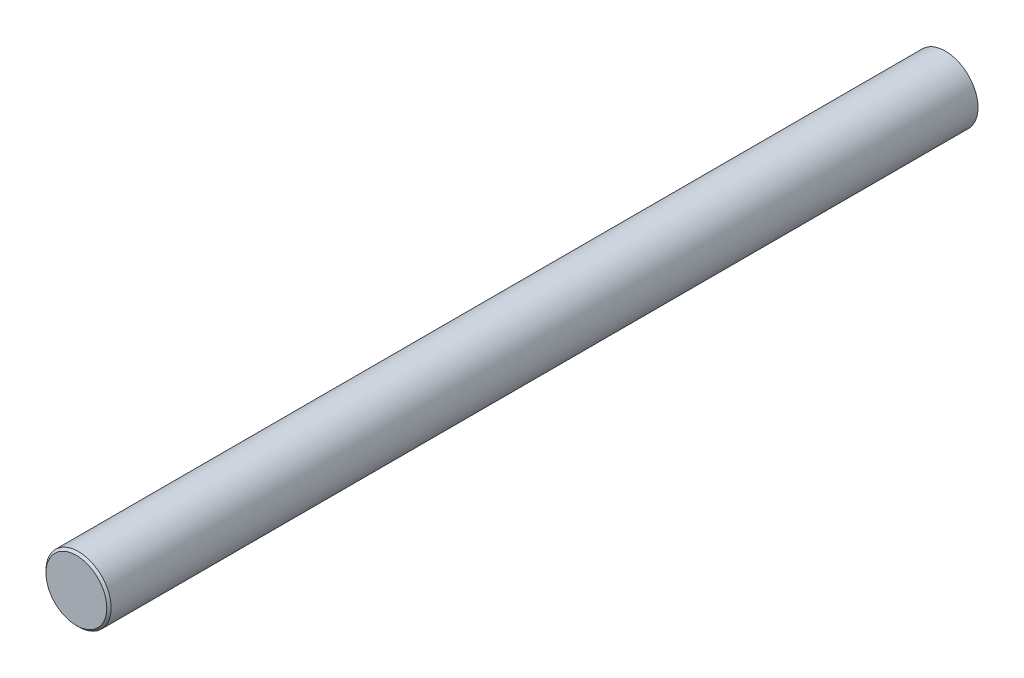
SolidWorks part; units mm, degrees
material "PW80:Mi:0:6:C1:0:1:2:Re:26:"
ref_plane "Plan1" through (0, 0, 0) normal (0, 0, 1) x (1, 0, 0)
ref_plane "Plan2" through (0, 0, 0) normal (0, 1, 0) x (1, 0, 0)
ref_plane "Plan3" through (0, 0, 0) normal (1, 0, 0) x (0, 0, -1)
sketch "Esquisse1" plane through (0, 0, 0) normal (0, 0, 1) x (1, 0, 0)
  circle A0 centre (0, 0) radius 15
extrude "Base-Extrusion" add sketch "Esquisse1" along normal blind 400
chamfer "Chanfrein1" distance 1 angle 45
